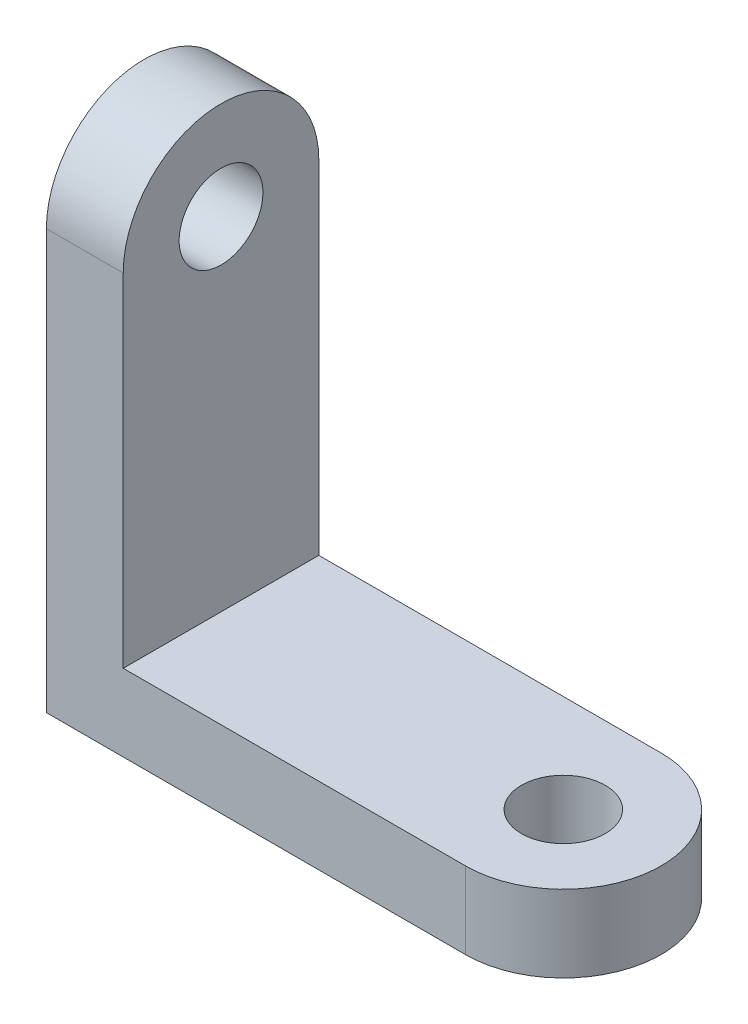
SolidWorks part; units mm, degrees
ref_plane "Front Plane" through (0, 0, 0) normal (0, 0, 1) x (1, 0, 0)
ref_plane "Top Plane" through (0, 0, 0) normal (0, 1, 0) x (1, 0, 0)
ref_plane "Right Plane" through (0, 0, 0) normal (1, 0, 0) x (0, 0, -1)
sketch "Sketch1" plane through (0, 0, 0) normal (0, 1, 0) x (1, 0, 0)
  line L1 (-7.5, 3.5) -> (7.5, 3.5)
  line L2 (-7.5, 3.5) -> (-7.5, -3.5)
  line L3 (-7.5, -3.5) -> (7.5, -3.5)
  arc A0 (7.5, 3.5) -> (7.5, -3.5) centre (7.5, 0) cw
  point P5 (-7.5, 0)
  point P6 (0, -3.5)
  dimension "D1" = 7
  dimension "D2" = 15
extrude "Boss-Extrude1" add sketch "Sketch1" along normal blind 2.75
sketch "Sketch3" plane through (0, 2.75, 0) normal (0, 1, 0) x (1, 0, 0)
  circle A0 centre (7.5, 0) radius 1.5
  dimension "D1" = 3
extrude "Cut-Extrude1" cut sketch "Sketch3" against normal blind 2.75
sketch "Sketch5" plane through (-7.5, 0, 0) normal (-1, 0, 0) x (0, 0, 1)
  line L1 (-3.5, 0) -> (3.5, 0)
  line L2 (-3.5, 0) -> (-3.5, 15)
  line L4 (3.5, 0) -> (3.5, 15)
  arc A0 (-3.5, 15) -> (3.5, 15) centre (0, 15) cw
  dimension "D1" = 15
extrude "Boss-Extrude2" add sketch "Sketch5" against normal blind 2.75
sketch "Sketch6" plane through (-4.75, 0, 0) normal (1, 0, 0) x (0, 0, -1)
  circle A0 centre (0, 15) radius 1.5
  dimension "D1" = 3
extrude "Cut-Extrude2" cut sketch "Sketch6" against normal blind 2.75
